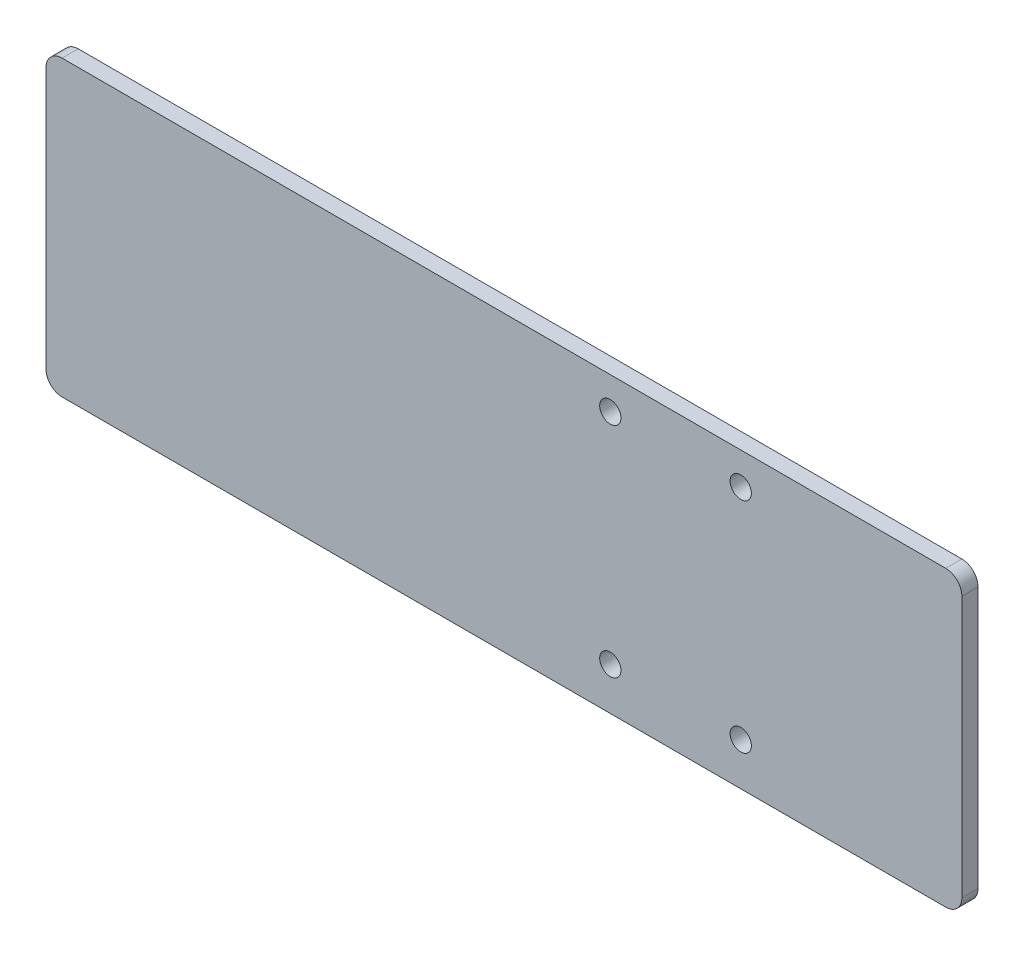
SolidWorks part; units mm, degrees
ref_plane "Front Plane" through (0, 0, 0) normal (0, 0, 1) x (1, 0, 0)
ref_plane "Top Plane" through (0, 0, 0) normal (0, 1, 0) x (1, 0, 0)
ref_plane "Right Plane" through (0, 0, 0) normal (1, 0, 0) x (0, 0, -1)
sketch "Sketch1" plane through (0, 0, 0) normal (0, 0, 1) x (1, 0, 0)
  line L1 (-137, -45.5) -> (137, -45.5)
  line L2 (-142, -40.5) -> (-142, 40.5)
  line L3 (-137, 45.5) -> (137, 45.5)
  line L4 (142, -40.5) -> (142, 40.5)
  line L5 (-142, -45.5) -> (142, 45.5) construction
  line L6 (-142, 45.5) -> (142, -45.5) construction
  arc A0 (142, 40.5) -> (137, 45.5) centre (137, 40.5) ccw
  arc A1 (142, -40.5) -> (137, -45.5) centre (137, -40.5) cw
  arc A2 (-137, -45.5) -> (-142, -40.5) centre (-137, -40.5) cw
  arc A3 (-142, 40.5) -> (-137, 45.5) centre (-137, 40.5) cw
  point P0 (0, 0)
  dimension "D3" = 5
  dimension "D1" = 91
  dimension "D2" = 284
extrude "Boss-Extrude1" add sketch "Sketch1" along normal blind 5
hole_wizard "M6 Clearance Hole2" positions "Sketch5" profile "Sketch4" hole size "M6" standard "ANSI Metric"
sketch "Sketch5" plane through (0, 0, 0) normal (0, 0, -1) x (-1, 0, 0)
  point P0 (-73.4316, -32.2992)
  point P2 (-32.9877, -32.2992)
  point P4 (-32.9877, 35.5092)
  point P6 (-73.4316, 35.5092)
sketch "Sketch4" plane through (73.4316, -32.2992, 0) normal (1, 0, 0) x (0, 1, 0)
  line L0 (0, 0) -> (0, 7.9828)
  line L1 (0, 7.9828) -> (3.3, 6)
  line L2 (3.3, 6) -> (3.3, 0)
  line L5 (3.3, 0) -> (0, 0)
  line L10 (0, 7.9828) -> (-3.3, 6) construction
  line L11 (0, -6.35) -> (0, 107.95) construction
  dimension "Hole Dia." = 6.6
  dimension "Hole Depth" = 6
  dimension "Drill Angle" = 118
